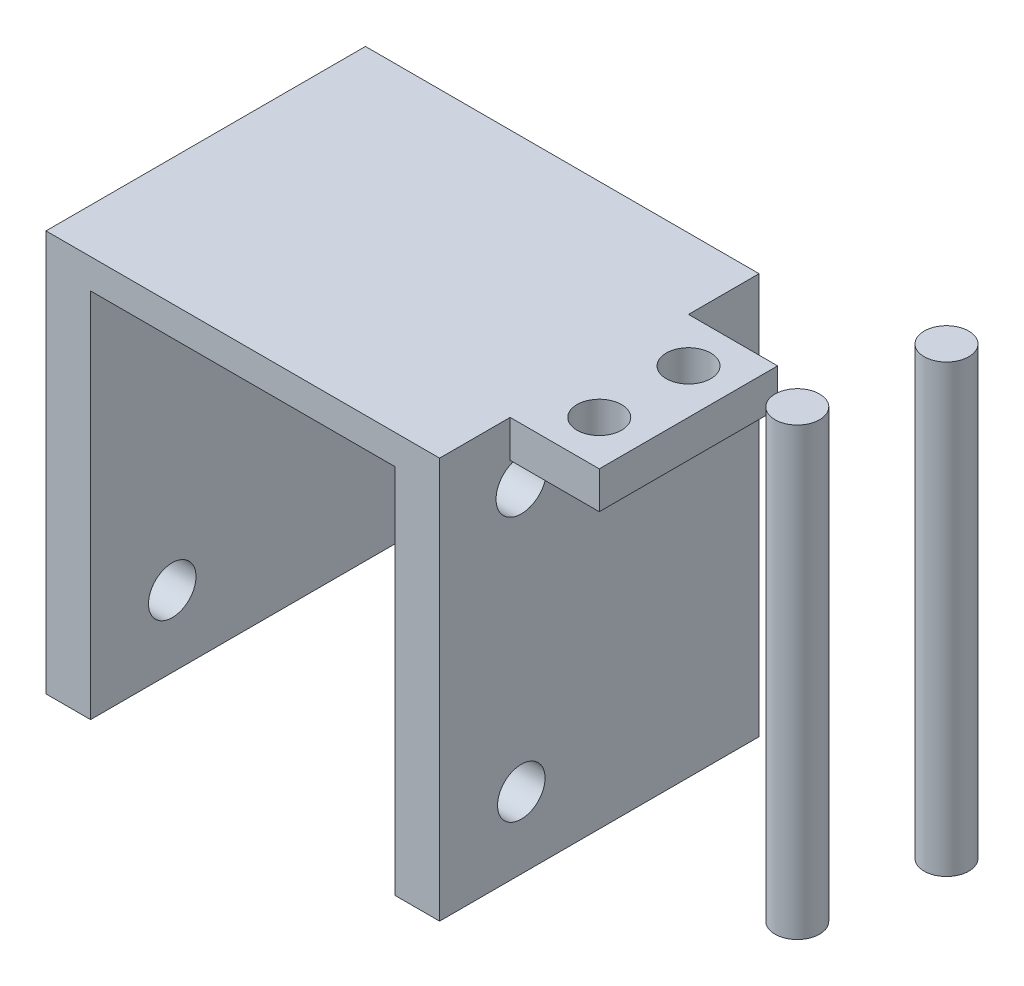
SolidWorks part; units mm, degrees
ref_plane "Front Plane" through (0, 0, 0) normal (0, 0, 1) x (1, 0, 0)
ref_plane "Top Plane" through (0, 0, 0) normal (0, 1, 0) x (1, 0, 0)
ref_plane "Right Plane" through (0, 0, 0) normal (1, 0, 0) x (0, 0, -1)
sketch "Sketch1" plane through (0, 0, 0) normal (0, 0, 1) x (1, 0, 0)
  line L1 (-2.1777, -34.964) -> (-28.6777, -34.964)
  line L2 (-2.1777, -34.964) -> (-2.1777, -7.964)
  line L3 (-2.1777, -7.964) -> (-28.6777, -7.964)
  line L4 (-28.6777, -34.964) -> (-28.6777, -7.964)
  line L5 (-2.1777, -34.964) -> (-28.6777, -7.964) construction
  line L6 (-2.1777, -7.964) -> (-28.6777, -34.964) construction
  point P0 (-15.4277, -21.464)
extrude "Boss-Extrude1" add sketch "Sketch1" along normal blind 36.7
sketch "Sketch2" plane through (0, 0, 0) normal (0, 0, -1) x (-1, 0, 0)
  line L0 (28.6777, -34.964) -> (2.1777, -34.964) construction
  line L1 (25.6777, -34.964) -> (5.1777, -34.964)
  line L2 (25.6777, -34.964) -> (25.6777, -9.964)
  line L3 (25.6777, -9.964) -> (5.1777, -9.964)
  line L4 (5.1777, -34.964) -> (5.1777, -9.964)
  line L5 (25.6777, -34.964) -> (5.1777, -9.964) construction
  line L6 (25.6777, -9.964) -> (5.1777, -34.964) construction
  line L9 (2.1777, -7.964) -> (28.6777, -7.964) construction
  line L10 (2.1777, -34.964) -> (2.1777, -7.964) construction
  line L11 (28.6777, -7.964) -> (28.6777, -34.964) construction
  point P0 (15.4277, -22.464)
  dimension "D1" = 0
  dimension "D2" = 3
  dimension "D3" = 3
  dimension "D4" = 2
extrude "Cut-Extrude1" cut sketch "Sketch2" against normal blind 36.7
sketch "Sketch3" plane through (-2.1777, 0, 0) normal (1, 0, 0) x (0, 0, -1)
  line L1 (-36.7, -34.964) -> (-36.7, -7.964) construction
  line L2 (-36.7, -9.964) -> (0, -9.964) construction
  circle A0 centre (-31.2, -12.264) radius 1.7
  circle A1 centre (-31.2, -30.164) radius 1.6
  dimension "D3" = 17.9
  dimension "D1" = 2.3
  dimension "D2" = 5.5
  dimension "D4" = 5.5
extrude "Cut-Extrude2" cut sketch "Sketch3" against normal blind 36.7
sketch "Sketch4" plane through (-2.1777, 0, 0) normal (1, 0, 0) x (0, 0, -1)
  line L1 (0, -34.964) -> (0, -7.964) construction
  line L2 (-36.7, -9.964) -> (0, -9.964) construction
  circle A0 centre (-12.0251, -21.164) radius 3
  dimension "D1" = 11.2
  dimension "D2" = 12.0251
extrude "Cut-Extrude3" cut sketch "Sketch4" against normal blind 36.7
sketch "Sketch8" plane through (0, -7.964, 0) normal (0, 1, 0) x (1, 0, 0)
  circle A0 centre (7.1574, -12.974) radius 1.5
  circle A1 centre (7.5744, -21.6698) radius 1.5
extrude "Boss-Extrude3" add sketch "Sketch8" against normal blind 30 separate body
sketch "Sketch9" plane through (0, 0, 0) normal (0, 0, -1) x (-1, 0, 0)
  line L1 (6.6484, -24.164) -> (0.7297, -24.164)
  line L2 (6.6484, -24.164) -> (6.6484, -18.164)
  line L3 (6.6484, -18.164) -> (0.7297, -18.164)
  line L4 (0.7297, -24.164) -> (0.7297, -18.164)
  line L5 (6.6484, -24.164) -> (0.7297, -18.164) construction
  line L6 (6.6484, -18.164) -> (0.7297, -24.164) construction
  line L7 (31.4578, -24.164) -> (24.7499, -24.164)
  line L8 (31.4578, -24.164) -> (31.4578, -18.164)
  line L9 (31.4578, -18.164) -> (24.7499, -18.164)
  line L10 (24.7499, -24.164) -> (24.7499, -18.164)
  line L11 (31.4578, -24.164) -> (24.7499, -18.164) construction
  line L12 (31.4578, -18.164) -> (24.7499, -24.164) construction
  line L13 (25.6777, -9.964) -> (5.1777, -9.964) construction
  point P0 (3.689, -21.164)
  point P5 (28.1039, -21.164)
  dimension "D1" = 14.2
  dimension "D2" = 14.2
extrude "Cut-Extrude4" cut sketch "Sketch9" against normal blind 12
sketch "Sketch11" plane through (-28.6777, 0, 0) normal (-1, 0, 0) x (0, 0, 1)
  line L0 (0, -7.964) -> (0, -18.164) construction
  line L1 (15.1914, -34.964) -> (0, -34.964)
  line L2 (15.1914, -34.964) -> (15.1914, 2.1035)
  line L3 (15.1914, 2.1035) -> (0, 2.1035)
  line L4 (0, -34.964) -> (0, 2.1035)
  line L5 (15.1914, -34.964) -> (0, 2.1035) construction
  line L6 (15.1914, 2.1035) -> (0, -34.964) construction
  line L7 (36.7, -34.964) -> (0, -34.964) construction
  point P0 (7.5957, -16.4302)
  dimension "D1" = 0
  dimension "D2" = 0
extrude "Cut-Extrude6" cut sketch "Sketch11" against normal blind 32
sketch "Sketch12" plane through (-28.6777, 0, 0) normal (-1, 0, 0) x (0, 0, 1)
  line L0 (36.7, -7.964) -> (15.1914, -7.964) construction
  line L1 (19.95, -7.964) -> (31.95, -7.964)
  line L2 (19.95, -7.964) -> (19.95, -10.464)
  line L3 (19.95, -10.464) -> (31.95, -10.464)
  line L4 (31.95, -7.964) -> (31.95, -10.464)
  line L5 (19.95, -7.964) -> (31.95, -10.464) construction
  line L6 (19.95, -10.464) -> (31.95, -7.964) construction
  line L7 (36.7, -7.964) -> (36.7, -34.964) construction
  point P0 (25.95, -9.214)
  dimension "D1" = 0
  dimension "D2" = 4.75
extrude "Boss-Extrude4" add sketch "Sketch12" along normal blind 6
sketch "Sketch13" plane through (0, -7.964, 0) normal (0, 1, 0) x (1, 0, 0)
  line L0 (-34.6777, -19.95) -> (-28.6777, -19.95) construction
  line L1 (-34.6777, -31.95) -> (-28.6777, -31.95) construction
  line L2 (-34.6777, -31.95) -> (-34.6777, -19.95) construction
  circle A0 centre (-31.6777, -22.95) radius 1.5
  circle A1 centre (-31.6777, -28.95) radius 1.5
  dimension "D1" = 3
  dimension "D2" = 3
  dimension "D3" = 3
  dimension "D4" = 3
extrude "Cut-Extrude7" cut sketch "Sketch13" against normal blind 6
move or copy body "Body-Move/Copy4" bodies to move or copy 115 copy yes number of copies 1 translate (-70.8216, 0, 0) parameters "D1"=70.8216, "D2"=0, "D3"=0
move or copy body "Body-Move/Copy5" bodies to move or copy 108 copy yes number of copies 1 translate (-69.7545, 0, 0) parameters "D1"=69.7545, "D2"=0, "D3"=0
move or copy body "Body-Move/Copy6" bodies to move or copy 109 copy yes number of copies 1 translate (-71.5211, 0, 0) parameters "D1"=71.5211, "D2"=0, "D3"=0
sketch "Sketch14" plane through (0, -7.964, 0) normal (0, 1, 0) x (1, 0, 0)
  line L0 (-99.4994, -19.95) -> (-99.4994, -15.1914) construction
  line L1 (-111.2318, -2.8793) -> (-99.4994, -2.8793)
  line L2 (-111.2318, -2.8793) -> (-111.2318, -34.8559)
  line L3 (-111.2318, -34.8559) -> (-99.4994, -34.8559)
  line L4 (-99.4994, -2.8793) -> (-99.4994, -34.8559)
  line L5 (-111.2318, -2.8793) -> (-99.4994, -34.8559) construction
  line L6 (-111.2318, -34.8559) -> (-99.4994, -2.8793) construction
  point P0 (-105.3656, -18.8676)
  dimension "D1" = 0
extrude "Cut-Extrude8" cut sketch "Sketch14" against normal blind 10
sketch "Sketch15" plane through (0, -7.964, 0) normal (0, 1, 0) x (1, 0, 0)
  line L0 (-72.9994, -36.7) -> (-72.9994, -15.1914) construction
  line L1 (-72.9994, -19.9414) -> (-66.9994, -19.9414)
  line L2 (-72.9994, -19.9414) -> (-72.9994, -31.95)
  line L3 (-72.9994, -31.95) -> (-66.9994, -31.95)
  line L4 (-66.9994, -19.9414) -> (-66.9994, -31.95)
  line L5 (-72.9994, -19.9414) -> (-66.9994, -31.95) construction
  line L6 (-72.9994, -31.95) -> (-66.9994, -19.9414) construction
  line L7 (-72.9994, -36.7) -> (-99.4994, -36.7) construction
  line L8 (-72.9994, -15.1914) -> (-99.4994, -15.1914) construction
  circle A0 centre (-69.9994, -22.9414) radius 1.5
  circle A1 centre (-69.9994, -28.95) radius 1.5
  point P0 (-69.9994, -25.9457)
  dimension "D4" = 3
  dimension "D5" = 3
  dimension "D6" = 3
  dimension "D7" = 3
  dimension "D1" = 0
  dimension "D2" = 4.75
  dimension "D3" = 4.75
extrude "Boss-Extrude5" add sketch "Sketch15" against normal blind 2.5
sketch "Sketch16" plane through (0, -7.964, 0) normal (0, 1, 0) x (1, 0, 0)
  line L1 (-38.9995, -5.9657) -> (15.9366, -5.9657)
  line L2 (-38.9995, -5.9657) -> (-38.9995, -41.2818)
  line L3 (-38.9995, -41.2818) -> (15.9366, -41.2818)
  line L4 (15.9366, -5.9657) -> (15.9366, -41.2818)
  line L5 (-38.9995, -5.9657) -> (15.9366, -41.2818) construction
  line L6 (-38.9995, -41.2818) -> (15.9366, -5.9657) construction
  point P0 (-11.5314, -23.6238)
extrude "Cut-Extrude9" cut sketch "Sketch16" against normal blind 50
